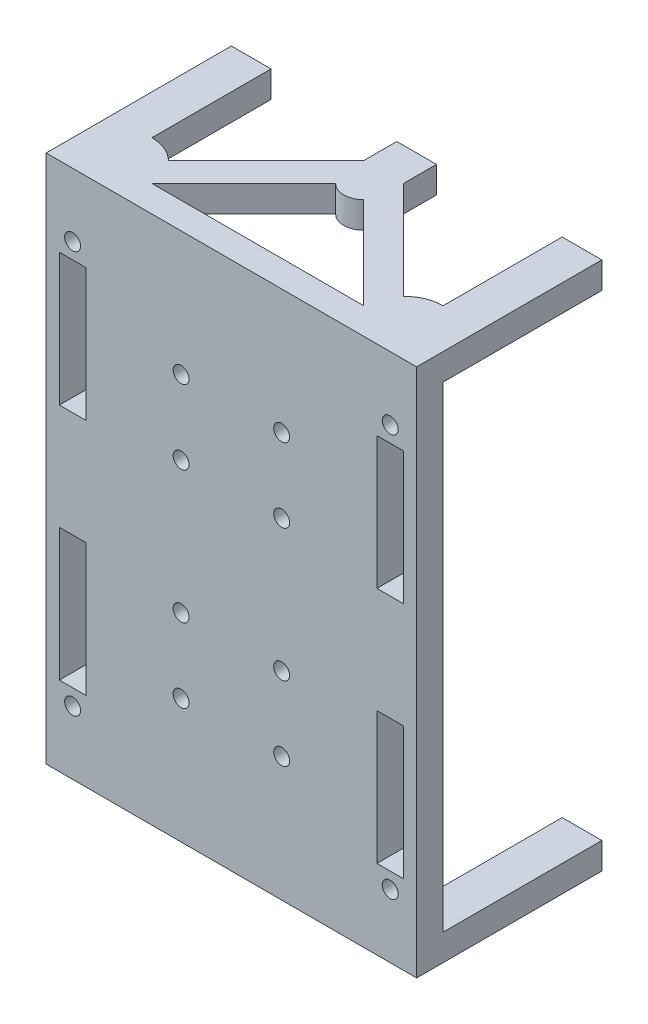
SolidWorks part; units mm, degrees
ref_plane "Front Plane" through (0, 0, 0) normal (0, 0, 1) x (1, 0, 0)
ref_plane "Top Plane" through (0, 0, 0) normal (0, 1, 0) x (1, 0, 0)
ref_plane "Right Plane" through (0, 0, 0) normal (1, 0, 0) x (0, 0, -1)
sketch "Sketch1" plane through (0, 0, 0) normal (0, 0, 1) x (1, 0, 0)
  line L1 (-35, -50) -> (35, -50)
  line L2 (-35, -50) -> (-35, 50)
  line L3 (-35, 50) -> (35, 50)
  line L4 (35, -50) -> (35, 50)
  line L5 (-35, -50) -> (35, 50) construction
  line L6 (-35, 50) -> (35, -50) construction
  point P0 (0, 0)
  dimension "D1" = 70
  dimension "D2" = 100
extrude "Boss-Extrude1" add sketch "Sketch1" along normal mid plane 5
sketch "Sketch2" plane through (0, 0, -2.5) normal (0, 0, -1) x (-1, 0, 0)
  line L0 (25, 26) -> (35, 50)
  line L1 (35, 50) -> (25, 50)
  line L2 (35, 50) -> (35, 26)
  line L3 (35, 26) -> (25, 26)
  line L4 (25, 50) -> (25, 26)
  line L5 (0, 50) -> (0, -50) construction
  line L6 (-35, 50) -> (35, 50) construction
  line L7 (35, -50) -> (-35, -50) construction
  line L8 (-35, 0) -> (35, 0) construction
  line L9 (-35, -50) -> (-35, 50) construction
  line L10 (35, 50) -> (35, -50) construction
  circle A0 centre (30, 38) radius 1.5
  circle A1 centre (-30, 38) radius 1.5
  circle A2 centre (30, -38) radius 1.5
  circle A3 centre (-30, -38) radius 1.5
  dimension "D3" = 3
  dimension "D1" = 24
  dimension "D2" = 10
extrude "Cut-Extrude1" cut sketch "Sketch2" against normal blind 10 contours A0 | A2 | A3 | A1
sketch "Sketch3" plane through (0, 50, 0) normal (0, 1, 0) x (1, 0, 0)
  line L0 (-35, 2.5) -> (-35, 32.5)
  line L1 (0, 2.5) -> (0, 18.75) construction
  line L2 (35, 2.5) -> (-35, 2.5) construction
  line L3 (-35, 32.5) -> (-27.5, 32.5)
  line L4 (-27.5, 32.5) -> (-27.5, 10)
  line L5 (-22.1967, 7.8033) -> (-3.75, 26.25)
  line L6 (-35, 2.5) -> (-20, 2.5)
  line L7 (-20, 2.5) -> (-2.6517, 19.8483)
  line L8 (20, 2.5) -> (35, 2.5)
  line L10 (-3.75, 32.5) -> (3.75, 32.5)
  line L11 (-3.75, 26.25) -> (-3.75, 32.5)
  line L14 (3.75, 26.25) -> (3.75, 32.5)
  line L15 (2.6517, 19.8483) -> (20, 2.5)
  line L16 (22.1967, 7.8033) -> (3.75, 26.25)
  line L17 (35, 32.5) -> (27.5, 32.5)
  line L18 (27.5, 32.5) -> (27.5, 10)
  line L19 (35, 2.5) -> (35, 32.5)
  line L20 (0, 22.5) -> (0, 51.9526) construction
  arc A1 (-22.1967, 7.8033) -> (-27.5, 10) centre (-27.5, 2.5) ccw
  arc A2 (22.1967, 7.8033) -> (27.5, 10) centre (27.5, 2.5) cw
  arc A3 (-2.6517, 19.8483) -> (2.6517, 19.8483) centre (0, 22.5) ccw
  point P22 (0, 32.5)
  dimension "D5" = 7.5
  dimension "D1" = 30
  dimension "D2" = 7.5
extrude "Boss-Extrude2" add sketch "Sketch3" against normal blind 5
mirror "Mirror1" about plane through (0, 0, 0) normal (0, 1, 0) of "Boss-Extrude2"
sketch "Sketch4" plane through (0, 0, -2.5) normal (0, 0, -1) x (-1, 0, 0)
  line L0 (-35, 0) -> (35, 0) construction
  line L1 (-35, -45) -> (-35, 45) construction
  line L2 (35, 45) -> (35, -45) construction
  line L3 (-11.5, 8) -> (-11.5, 12.5)
  line L4 (32.5, 35) -> (27.5, 35)
  line L5 (-11.5, 37) -> (11.5, 37)
  line L6 (-11.5, 37) -> (-11.5, 8)
  line L7 (-11.5, 8) -> (11.5, 8)
  line L8 (11.5, 37) -> (11.5, 8)
  line L9 (-11.5, 37) -> (11.5, 8) construction
  line L10 (-11.5, 8) -> (11.5, 37) construction
  line L11 (27.5, 10) -> (27.5, 35)
  line L12 (0, 22.5) -> (0, 45) construction
  line L13 (-32.5, 10) -> (-27.5, 10)
  line L14 (-32.5, 10) -> (-32.5, 35)
  line L15 (-32.5, 35) -> (-27.5, 35)
  line L16 (-27.5, 10) -> (-27.5, 35)
  line L17 (-32.5, 10) -> (-27.5, 35) construction
  line L18 (-32.5, 35) -> (-27.5, 10) construction
  line L19 (-3.75, 45) -> (3.75, 45) construction
  line L20 (0, 45) -> (0, 0) construction
  line L21 (-11.5, 12.5) -> (-9.5, 12.5)
  line L22 (-9.5, 12.5) -> (-9.5, 26.5)
  line L23 (32.5, 10) -> (27.5, 10)
  line L24 (32.5, 10) -> (32.5, 35)
  line L25 (32.5, -10) -> (32.5, -35)
  line L26 (32.5, -10) -> (27.5, -10)
  line L27 (27.5, -10) -> (27.5, -35)
  line L28 (32.5, -35) -> (27.5, -35)
  line L29 (-32.5, -35) -> (-27.5, -35)
  line L30 (-27.5, -10) -> (-27.5, -35)
  line L31 (-32.5, -10) -> (-27.5, -10)
  line L32 (-32.5, -10) -> (-32.5, -35)
  circle A0 centre (-9.5, 12.5) radius 1.5
  circle A1 centre (-9.5, 26.5) radius 1.5
  circle A2 centre (9.5, 12.5) radius 1.5
  circle A3 centre (9.5, 26.5) radius 1.5
  circle A4 centre (9.5, -12.5) radius 1.5
  circle A5 centre (9.5, -26.5) radius 1.5
  circle A6 centre (-9.5, -26.5) radius 1.5
  circle A7 centre (-9.5, -12.5) radius 1.5
  dimension "D8" = 3
  dimension "D10" = 3
  dimension "D1" = 22.5
  dimension "D2" = 23
  dimension "D3" = 29
  dimension "D4" = 5
  dimension "D5" = 25
  dimension "D6" = 4.5
  dimension "D7" = 2
  dimension "D9" = 14
extrude "Cut-Extrude2" cut sketch "Sketch4" against normal blind 5 contours L31 L32 L29 L30 | A6 | A7 | A4 | A5 | L27 L28 L25 L26 | L11 L4 L24 L23 | A2 | A3 | A1 | A0 | L16 L15 L14 L13
sketch "Sketch7" plane through (0, 0, -32.5) normal (0, 0, -1) x (-1, 0, 0)
  line L0 (-3.75, 50) -> (3.75, 45)
  line L1 (-35, 50) -> (-27.5, 45)
  line L2 (35, 50) -> (27.5, 45)
  line L3 (27.5, 45) -> (27.5, 50) construction
  line L4 (27.5, 45) -> (35, 45) construction
  circle A0 centre (0, 47.5) radius 1.5
  circle A1 centre (-31.25, 47.5) radius 1.5
  circle A2 centre (31.25, 47.5) radius 1.5
  dimension "D1" = 3
  dimension "D2" = 3
  dimension "D3" = 3
extrude "Cut-Extrude3" cut sketch "Sketch7" against normal blind 5 contours A1 | A0 | A2
mirror "Mirror2" about plane through (0, 0, 0) normal (0, 1, 0) of "Cut-Extrude3"
